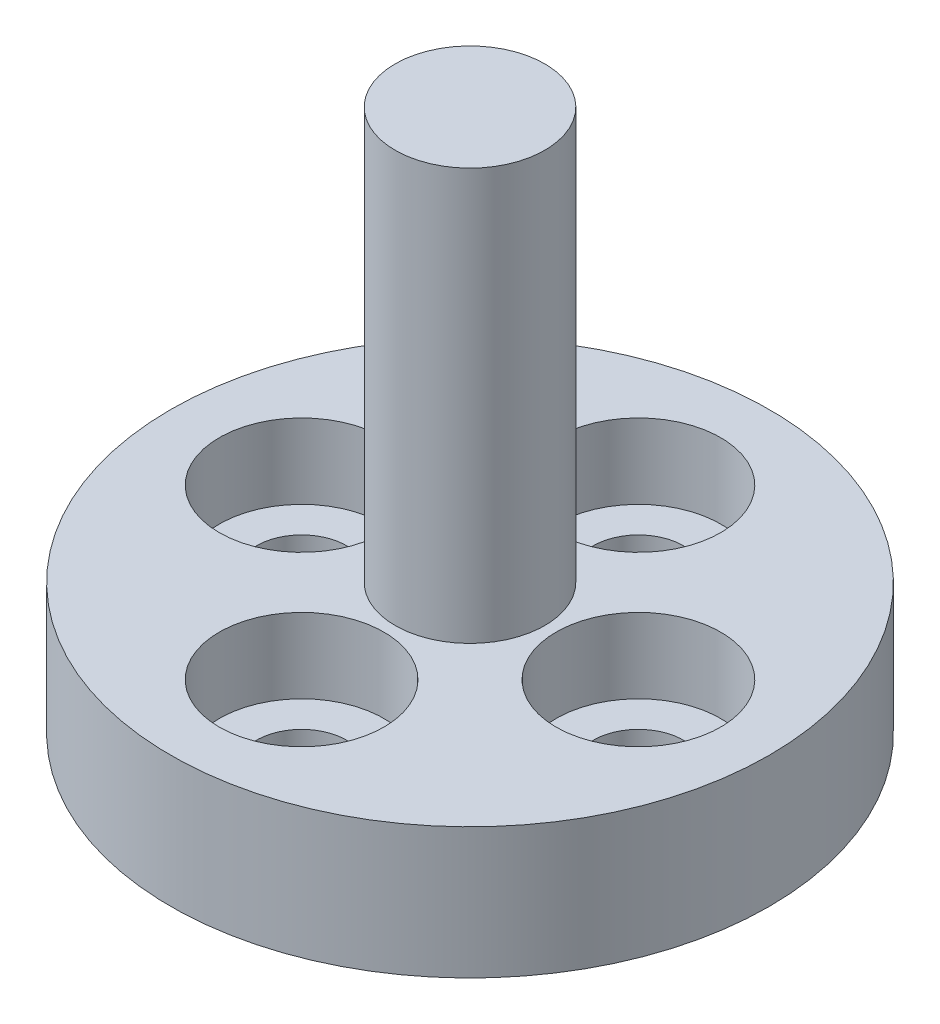
SolidWorks part; units mm, degrees
ref_plane "Front Plane" through (0, 0, 0) normal (0, 0, 1) x (1, 0, 0)
ref_plane "Top Plane" through (0, 0, 0) normal (0, 1, 0) x (1, 0, 0)
ref_plane "Right Plane" through (0, 0, 0) normal (1, 0, 0) x (0, 0, -1)
sketch "Sketch1" plane through (0, 0, 0) normal (0, 0, 1) x (1, 0, 0)
  line L0 (0, 0) -> (8, 0)
  line L1 (8, 0) -> (8, 3.5)
  line L2 (8, 3.5) -> (2, 3.5)
  line L3 (2, 3.5) -> (2, 14.5)
  line L4 (2, 14.5) -> (0, 14.5)
  line L5 (0, 14.5) -> (0, 0)
  dimension "D1" = 8
  dimension "D2" = 14.5
  dimension "D3" = 11
  dimension "D4" = 2
revolve "Revolve1" add sketch "Sketch1" angle 360 about L5
sketch "Sketch2" plane through (0, 14.5, 0) normal (0, 1, 0) x (1, 0, 0)
  circle A0 centre (0, 0) radius 4.5
  dimension "D1" = 9
hole_wizard "CBORE for M2 SHCS1" positions "Sketch3" profile "Sketch4" counterbore size "M2" standard "ANSI Metric" end condition through all
sketch "Sketch3" plane through (0, 3.5, 0) normal (0, 1, 0) x (1, 0, 0)
  circle A0 centre (0, 0) radius 4.5 construction
  point P0 (-4.5, 0)
  point P4 (0, 4.5)
  point P6 (4.5, 0)
  point P8 (0, -4.5)
sketch "Sketch4" plane through (-4.5, 3.5, 0) normal (1, 0, 0) x (0, 0, 1)
  line L0 (0, 0) -> (0, 3.5)
  line L1 (0, 3.5) -> (1.2, 3.5)
  line L3 (1.2, 3.5) -> (1.2, 2)
  line L4 (1.2, 2) -> (2.2, 2)
  line L5 (2.2, 2) -> (2.2, 0)
  line L7 (2.2, 0) -> (0, 0)
  line L11 (0, -6.35) -> (0, 107.95) construction
  dimension "Thru Hole Dia." = 2.4
  dimension "Thru Hole Depth" = 3.5
  dimension "C'Bore Dia." = 4.4
  dimension "C'Bore Depth" = 2
